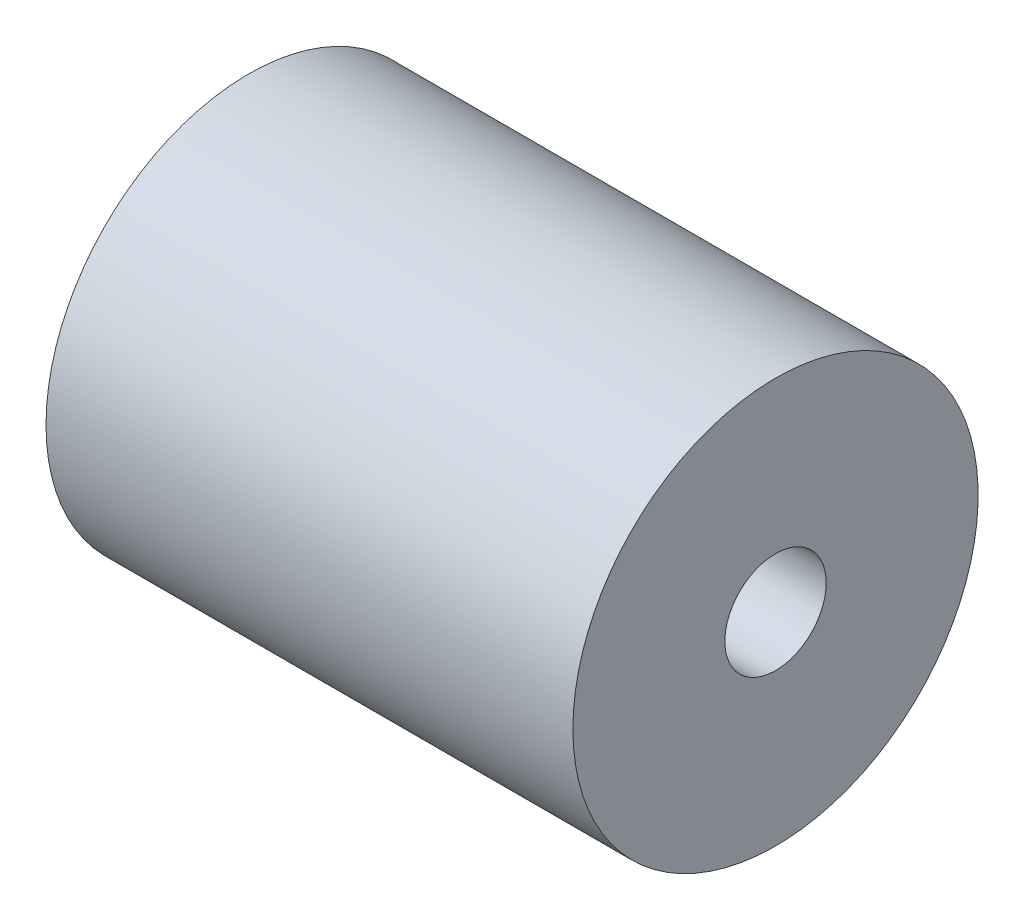
SolidWorks part; units mm, degrees
ref_plane "Front Plane" through (0, 0, 0) normal (0, 0, 1) x (1, 0, 0)
ref_plane "Top Plane" through (0, 0, 0) normal (0, 1, 0) x (1, 0, 0)
ref_plane "Right Plane" through (0, 0, 0) normal (1, 0, 0) x (0, 0, -1)
sketch "Sketch1" plane through (0, 0, 0) normal (1, 0, 0) x (0, 0, -1)
  circle A0 centre (0, 0) radius 10
  dimension "D1" = 20
extrude "Boss-Extrude1" add sketch "Sketch1" along normal mid plane 26
sketch "Sketch2" plane through (13, 0, 0) normal (1, 0, 0) x (0, 0, -1)
  circle A0 centre (0, 0) radius 2.5
  dimension "D1" = 5
extrude "Cut-Extrude1" cut sketch "Sketch2" against normal blind 13
sketch "Sketch3" plane through (-13, 0, 0) normal (-1, 0, 0) x (0, 0, 1)
  circle A0 centre (0, 0) radius 4
  dimension "D1" = 8
extrude "Cut-Extrude2" cut sketch "Sketch3" against normal blind 13
